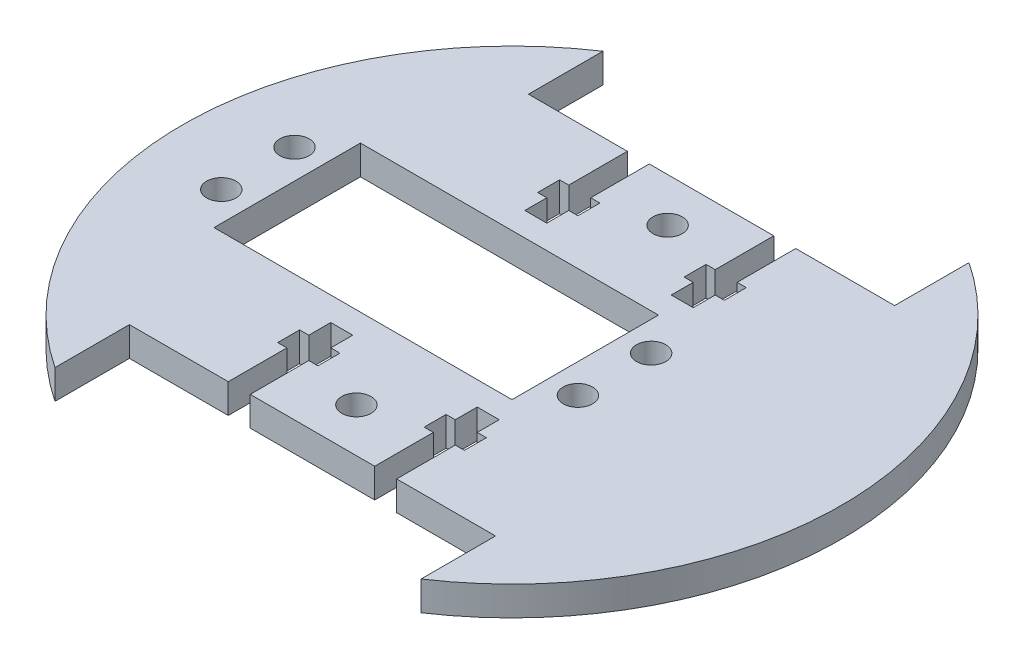
SolidWorks part; units mm, degrees
material "Acrílico (Impacto medio-alto)"
ref_plane "Piano frontale" through (0, 0, 0) normal (0, 0, 1) x (1, 0, 0)
ref_plane "Piano superiore" through (0, 0, 0) normal (0, 1, 0) x (1, 0, 0)
ref_plane "Piano destro" through (0, 0, 0) normal (1, 0, 0) x (0, 0, -1)
sketch "Schizzo1" plane through (0, 0, 0) normal (0, 1, 0) x (1, 0, 0)
  line L0 (-42.1632, 0) -> (43.9871, 0) construction
  line L1 (0, 27.25) -> (0, 0) construction
  line L2 (-25, 37.4166) -> (-25, 27.25)
  line L3 (-25, 27.25) -> (25, 27.25)
  line L4 (25, 37.4166) -> (25, 27.25)
  line L5 (0, 0) -> (0, -27.25) construction
  line L8 (-25, -37.4166) -> (-25, -27.25)
  line L9 (-25, -27.25) -> (25, -27.25)
  line L10 (25, -37.4166) -> (25, -27.25)
  arc A0 (-25, 37.4166) -> (-25, -37.4166) centre (0, 0) ccw
  arc A1 (25, -37.4166) -> (25, 37.4166) centre (0, 0) ccw
  point P3 (0, 45)
  point P8 (0, -45)
  dimension "D1" = 90
  dimension "D2" = 54.5
  dimension "D3" = 25
  dimension "D4" = 25
extrude "Estrusione-Estrusione1" add sketch "Schizzo1" along normal mid plane 4
sketch "Croquis1" plane through (0, -2, 0) normal (0, -1, 0) x (1, 0, 0)
  line L0 (-25, 27.25) -> (25, 27.25) construction
  line L1 (-11.5, 27.25) -> (-8.5, 27.25)
  line L2 (-11.5, 27.25) -> (-11.5, 19.25)
  line L3 (-11.5, 19.25) -> (-8.5, 19.25)
  line L4 (-8.5, 27.25) -> (-8.5, 19.25)
  line L5 (8.5, 27.25) -> (11.5, 27.25)
  line L6 (8.5, 27.25) -> (8.5, 19.25)
  line L7 (8.5, 19.25) -> (11.5, 19.25)
  line L8 (11.5, 27.25) -> (11.5, 19.25)
  line L9 (8.5, 31.25) -> (8.5, 27.25) construction
  line L10 (-11.5, 31.25) -> (-11.5, 27.25) construction
  line L11 (11.5, 27.25) -> (11.5, 31.25) construction
  line L12 (-12.75, 16.25) -> (-12.75, 19.25)
  line L13 (-12.75, 16.25) -> (-7.25, 16.25)
  line L14 (-12.75, 19.25) -> (-7.25, 19.25)
  line L15 (-7.25, 16.25) -> (-7.25, 19.25)
  line L16 (-12.75, 16.25) -> (-7.25, 19.25) construction
  line L17 (-12.75, 19.25) -> (-7.25, 16.25) construction
  line L18 (8.6009, 19.25) -> (11.3991, 19.25)
  line L19 (7.25, 16.25) -> (7.25, 19.25)
  line L20 (7.25, 16.25) -> (12.75, 16.25)
  line L21 (7.25, 19.25) -> (12.75, 19.25)
  line L22 (12.75, 16.25) -> (12.75, 19.25)
  line L23 (7.25, 16.25) -> (12.75, 19.25) construction
  line L24 (7.25, 19.25) -> (12.75, 16.25) construction
  line L25 (-45, 0) -> (45, 0) construction
  line L26 (-11.5, 16.25) -> (-8.5, 16.25)
  line L27 (-11.5, 16.25) -> (-11.5, 13.25)
  line L28 (-11.5, 13.25) -> (-8.5, 13.25)
  line L29 (-8.5, 16.25) -> (-8.5, 13.25)
  line L30 (8.5, 16.25) -> (11.5, 16.25)
  line L31 (8.5, 16.25) -> (8.5, 13.25)
  line L32 (8.5, 13.25) -> (11.5, 13.25)
  line L33 (11.5, 16.25) -> (11.5, 13.25)
  line L34 (7.25, -19.25) -> (12.75, -16.25) construction
  line L35 (7.25, -16.25) -> (12.75, -19.25) construction
  line L36 (-12.75, -19.25) -> (-7.25, -16.25) construction
  line L37 (-12.75, -16.25) -> (-7.25, -19.25) construction
  line L38 (11.5, -16.25) -> (11.5, -13.25)
  line L39 (8.5, -13.25) -> (11.5, -13.25)
  line L40 (8.5, -16.25) -> (8.5, -13.25)
  line L41 (8.5, -16.25) -> (11.5, -16.25)
  line L42 (-8.5, -16.25) -> (-8.5, -13.25)
  line L43 (-11.5, -13.25) -> (-8.5, -13.25)
  line L44 (-11.5, -16.25) -> (-11.5, -13.25)
  line L45 (-11.5, -16.25) -> (-8.5, -16.25)
  line L46 (12.75, -16.25) -> (12.75, -19.25)
  line L47 (7.25, -19.25) -> (12.75, -19.25)
  line L48 (7.25, -16.25) -> (12.75, -16.25)
  line L49 (7.25, -16.25) -> (7.25, -19.25)
  line L50 (8.6009, -19.25) -> (11.3991, -19.25)
  line L51 (-7.25, -16.25) -> (-7.25, -19.25)
  line L52 (-12.75, -19.25) -> (-7.25, -19.25)
  line L53 (-12.75, -16.25) -> (-7.25, -16.25)
  line L54 (-12.75, -16.25) -> (-12.75, -19.25)
  line L55 (11.5, -27.25) -> (11.5, -19.25)
  line L56 (8.5, -19.25) -> (11.5, -19.25)
  line L57 (8.5, -27.25) -> (8.5, -19.25)
  line L58 (8.5, -27.25) -> (11.5, -27.25)
  line L59 (-8.5, -27.25) -> (-8.5, -19.25)
  line L60 (-11.5, -19.25) -> (-8.5, -19.25)
  line L61 (-11.5, -27.25) -> (-11.5, -19.25)
  line L62 (-11.5, -27.25) -> (-8.5, -27.25)
  arc A0 (-25, 37.4166) -> (-25, -37.4166) centre (0, 0) ccw construction
  arc A1 (25, -37.4166) -> (25, 37.4166) centre (0, 0) ccw construction
  point P17 (-10, 17.75)
  point P18 (-10, 19.25)
  point P26 (10, 17.75)
  point P27 (10, 19.25)
  point P32 (10, 19.25)
  point P75 (10, -17.75)
  point P76 (-10, -17.75)
  line M3 (25, 27.25) -> (-25, 27.25)
  line M7 (-25, -27.25) -> (25, -27.25)
  dimension "D1" = 17
  dimension "D2" = 8
  dimension "D3" = 5.5
  dimension "D4" = 3
  dimension "D5" = 5.5
  dimension "D6" = 3
  dimension "D7" = 3
  dimension "D8" = 3
extrude "Cortar-Extruir4" cut sketch "Croquis1" against normal blind 10 contours L4 L2 L3 M3 | L13 L15 L14 L3 L12 | L33 L20 L31 L32 | L8 L6 L7 M3 | L44 L45 L42 L43 | L53 L54 L52 L51 L45 | L48 L49 L47 L46 L41 | L40 L41 L38 L39 | L57 L55 L47 M7 | L61 L59 L52 M7 | L27 L28 L29 L26
sketch "Croquis2" plane through (0, 2, 0) normal (0, 1, 0) x (1, 0, 0)
  line L0 (8.5, 27.25) -> (-8.5, 27.25) construction
  line L1 (-30.7, 10) -> (10, 10)
  line L2 (-30.7, 10) -> (-30.7, -10)
  line L3 (-30.7, -10) -> (10, -10)
  line L4 (10, 10) -> (10, -10)
  line L5 (-8.5, -27.25) -> (8.5, -27.25) construction
  circle A0 centre (-34.7, 5) radius 2
  circle A1 centre (-34.7, -5) radius 2 construction
  circle A2 centre (-34.7, -5) radius 2
  circle A3 centre (14, 5) radius 2 construction
  circle A4 centre (14, -5) radius 2 construction
  circle A5 centre (14, 5) radius 2
  circle A6 centre (14, -5) radius 2
  circle A7 centre (0, 21.25) radius 2
  circle A8 centre (0, -21.25) radius 2
  dimension "D1" = 4
  dimension "D2" = 6
  dimension "D3" = 6
extrude "Cortar-Extruir5" cut sketch "Croquis2" against normal through all
